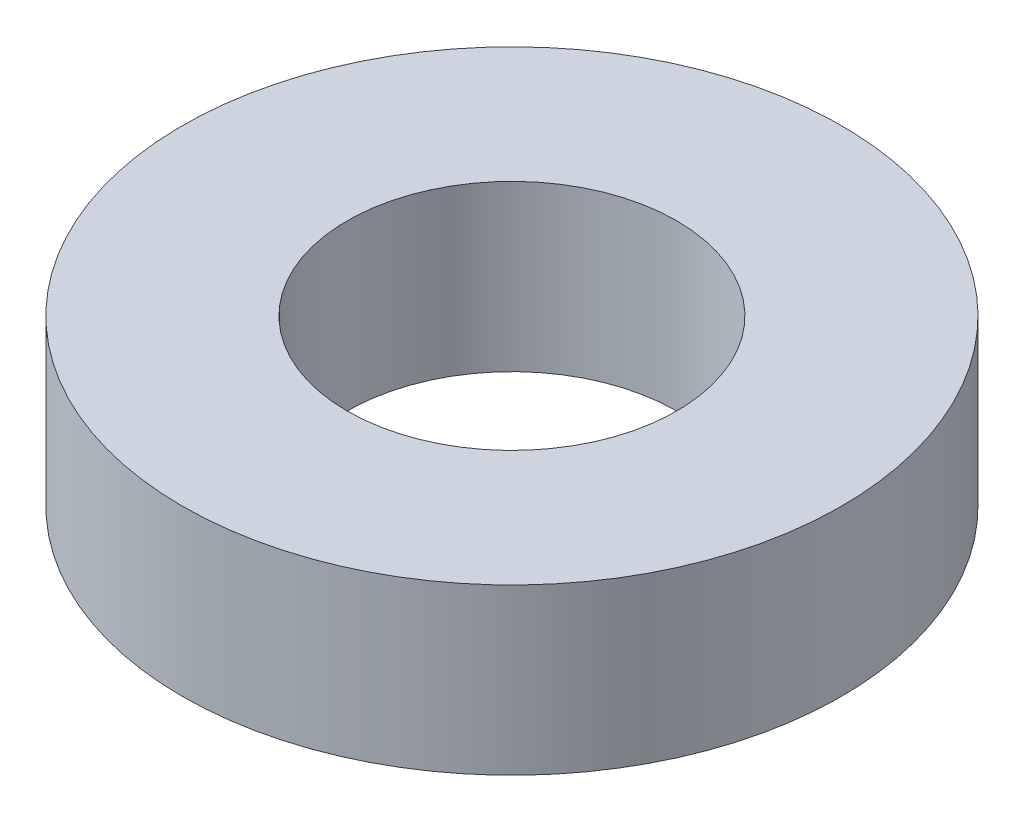
SolidWorks part; units mm, degrees
material "不锈钢 (铁素体)"
ref_plane "前视基准面" through (0, 0, 0) normal (0, 0, 1) x (1, 0, 0)
ref_plane "上视基准面" through (0, 0, 0) normal (0, 1, 0) x (1, 0, 0)
ref_plane "右视基准面" through (0, 0, 0) normal (1, 0, 0) x (0, 0, -1)
sketch "草图1" plane through (0, 0, 0) normal (0, 1, 0) x (1, 0, 0)
  circle A0 centre (0, 0) radius 4
  circle A1 centre (0, 0) radius 8
  dimension "D1" = 8
  dimension "D2" = 16
extrude "凸台-拉伸1" add sketch "草图1" along normal blind 4
